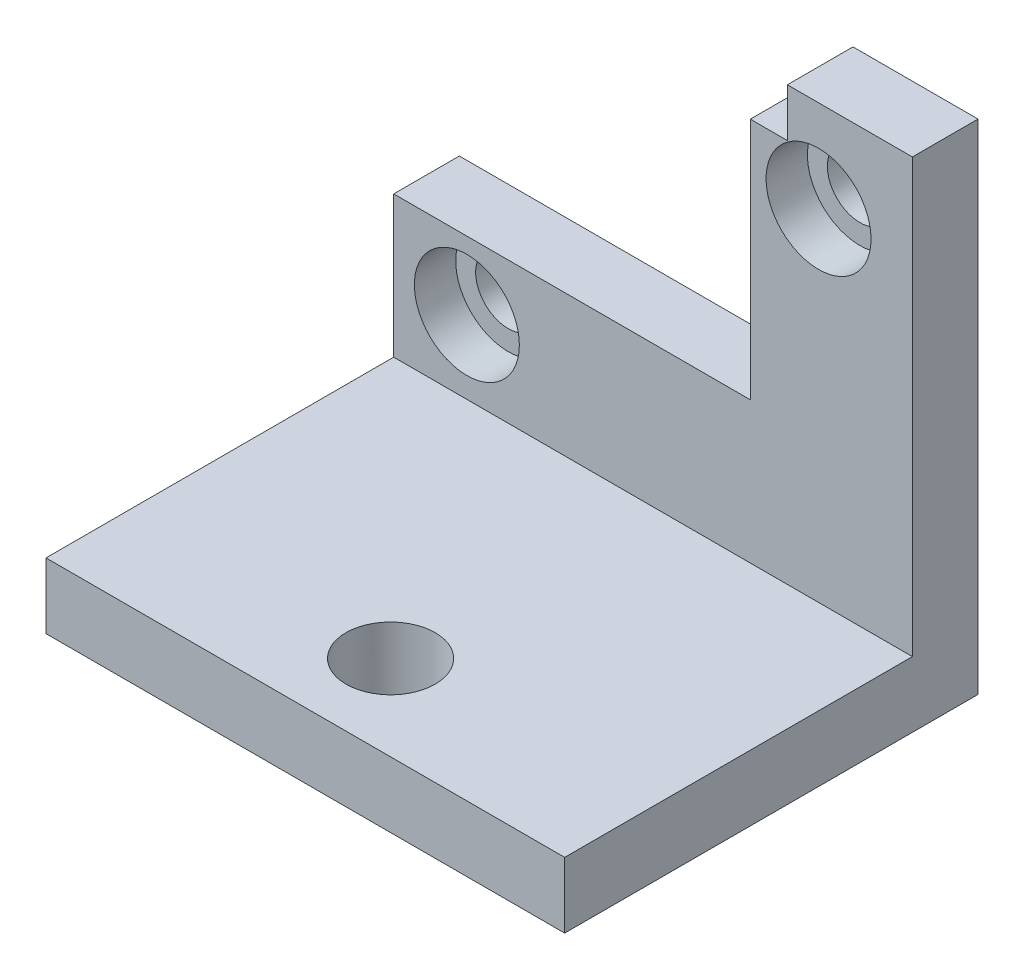
SolidWorks part; units mm, degrees
ref_plane "Front Plane" through (0, 0, 0) normal (0, 0, 1) x (1, 0, 0)
ref_plane "Top Plane" through (0, 0, 0) normal (0, 1, 0) x (1, 0, 0)
ref_plane "Right Plane" through (0, 0, 0) normal (1, 0, 0) x (0, 0, -1)
sketch "Sketch2" plane through (0, 0, 0) normal (0, 0, 1) x (1, 0, 0)
  line L0 (4.3952, 7.8274) -> (4.3952, -1.4384)
  line L1 (4.3952, -1.4384) -> (-11.8608, -1.4384)
  line L2 (-11.8608, -1.4384) -> (-11.8608, -8.2804)
  line L3 (-11.8608, -8.2804) -> (12.2372, -8.2804)
  line L4 (12.2372, -8.2804) -> (12.2372, 12.6586)
  line L5 (12.2372, 12.6586) -> (7.6972, 12.6586)
  line L7 (7.6972, 12.6586) -> (6.1882, 12.6586)
  line L8 (-11.8608, -1.4384) -> (-12.8608, -1.4384)
  line L9 (-11.8608, -1.4384) -> (-11.8608, -8.2804)
  line L10 (-11.8608, -8.2804) -> (-12.8608, -8.2804)
  line L11 (-12.8608, -1.4384) -> (-12.8608, -8.2804)
  line L12 (4.3952, 10.3218) -> (4.3952, 7.8274)
  line L13 (4.3952, 10.3218) -> (6.1882, 10.3218)
  line L14 (6.1882, 10.3218) -> (6.1882, 12.6586)
  circle A0 centre (7.6972, 8.2136) radius 1.5748
  circle A1 centre (-9.3208, -4.7404) radius 1.5748
  point P0 (6.4597, 9.1875)
  dimension "D5" = 16.494
  dimension "D1" = 1
  dimension "D2" = 6.842
  dimension "D3" = 20.939
  dimension "D4" = 24.098
  dimension "D6" = 2.54
  dimension "D7" = 3.54
  dimension "D8" = 17.018
extrude "Boss-Extrude1" add sketch "Sketch2" along normal blind 3.175 contours A0 | L8 L11 L10 L2 | A1
sketch "Sketch3" plane through (0, 0, 0) normal (0, 0, -1) x (-1, 0, 0)
  line L6 (-12.2372, -8.2804) -> (12.8608, -8.2804)
  line L7 (-12.2372, -8.2804) -> (-12.2372, -11.4554)
  line L8 (-12.2372, -11.4554) -> (12.8608, -11.4554)
  line L9 (12.8608, -8.2804) -> (12.8608, -11.4554)
  dimension "D1" = 3.175
extrude "Boss-Extrude3" add sketch "Sketch3" against normal blind 20
sketch "Sketch4" plane through (0, -11.4554, 0) normal (0, -1, 0) x (1, 0, 0)
  line L0 (12.2372, 0) -> (-12.8608, 0) construction
  line L1 (-0.3118, 20) -> (-0.3118, 3.0754) construction
  line L2 (12.2372, 20) -> (-12.8608, 20) construction
  circle A0 centre (-0.3118, 15.875) radius 2.159
  point P8 (0, 0)
  dimension "D1" = 4.318
  dimension "D2" = 15.875
extrude "Cut-Extrude1" cut sketch "Sketch4" against normal through all
sketch "Sketch5" plane through (0, 0, 3.175) normal (0, 0, 1) x (1, 0, 0)
  circle A0 centre (7.6972, 8.2136) radius 2.54
  circle A1 centre (-9.3208, -4.7404) radius 2.54
  dimension "D1" = 5.08
  dimension "D2" = 5.08
extrude "Cut-Extrude2" cut sketch "Sketch5" against normal blind 2
